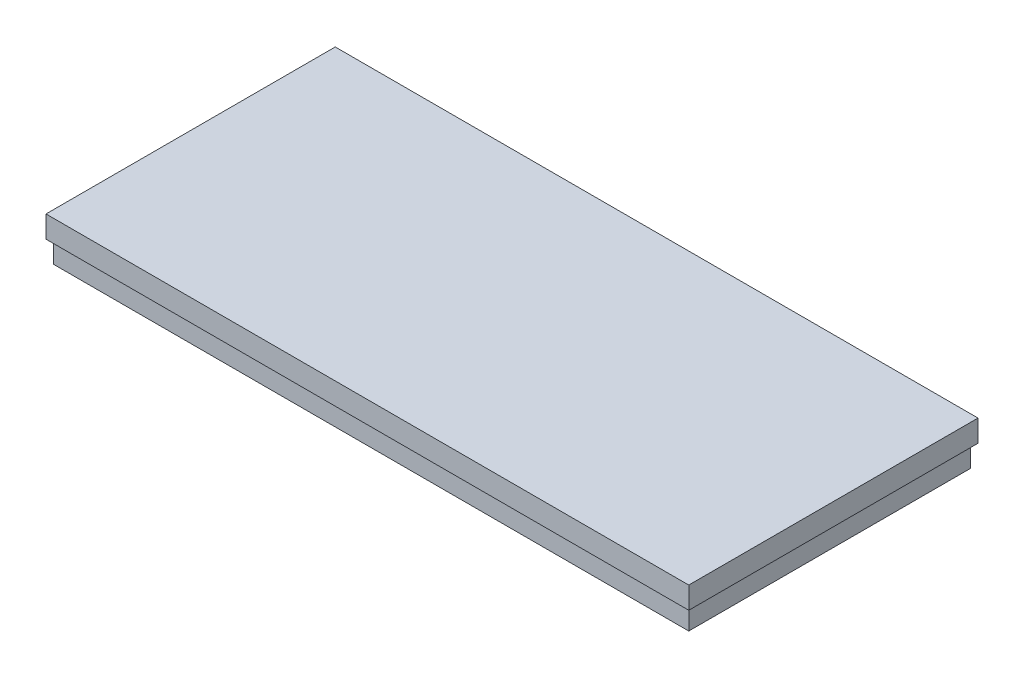
SolidWorks part; units mm, degrees
ref_plane "Front Plane" through (0, 0, 0) normal (0, 0, 1) x (1, 0, 0)
ref_plane "Top Plane" through (0, 0, 0) normal (0, 1, 0) x (1, 0, 0)
ref_plane "Right Plane" through (0, 0, 0) normal (1, 0, 0) x (0, 0, -1)
sketch "Sketch3" plane through (0, 0, 0) normal (0, 1, 0) x (1, 0, 0)
  line L1 (198.6285, -46.0226) -> (1.0285, -46.0226)
  line L2 (198.6285, -46.0226) -> (198.6285, -133.6226)
  line L3 (198.6285, -133.6226) -> (1.0285, -133.6226)
  line L4 (1.0285, -46.0226) -> (1.0285, -133.6226)
  dimension "D1" = 197.6
  dimension "D2" = 87.6
extrude "Boss-Extrude2" add sketch "Sketch3" along normal blind 6.8 separate body
sketch "Sketch4" plane through (0, 6.8, 0) normal (0, 1, 0) x (1, 0, 0)
  line L0 (1.0285, -46.0226) -> (198.6285, -133.6226) construction
  line L1 (1.0285, -133.6226) -> (198.6285, -46.0226) construction
  line L3 (-0.1715, -44.8226) -> (199.8285, -44.8226)
  line L4 (-0.1715, -44.8226) -> (-0.1715, -134.8226)
  line L5 (-0.1715, -134.8226) -> (199.8285, -134.8226)
  line L6 (199.8285, -44.8226) -> (199.8285, -134.8226)
  line L7 (-0.1715, -44.8226) -> (199.8285, -134.8226) construction
  line L8 (-0.1715, -134.8226) -> (199.8285, -44.8226) construction
  point P8 (99.8285, -89.8226)
  dimension "D1" = 200
  dimension "D2" = 90
extrude "Boss-Extrude3" add sketch "Sketch4" along normal blind 6.8
